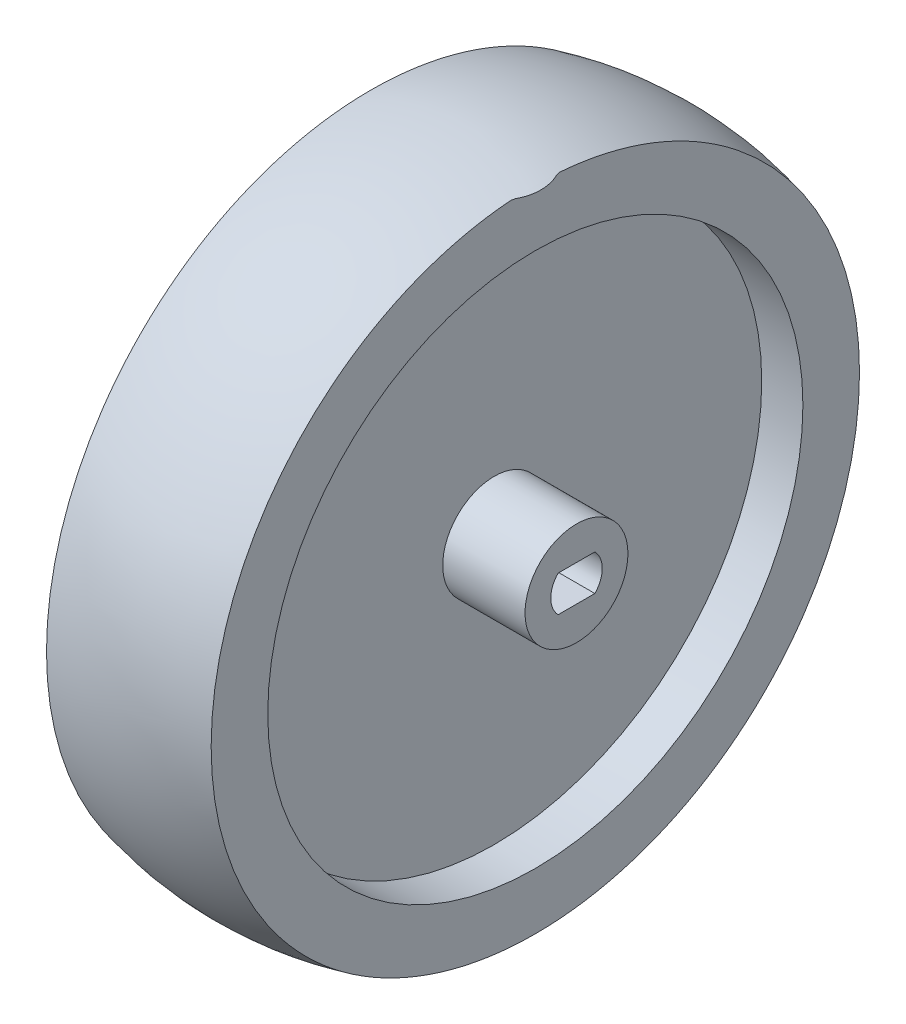
SolidWorks part; units mm, degrees
ref_plane "前视基准面" through (0, 0, 0) normal (0, 0, 1) x (1, 0, 0)
ref_plane "上视基准面" through (0, 0, 0) normal (0, 1, 0) x (1, 0, 0)
ref_plane "右视基准面" through (0, 0, 0) normal (1, 0, 0) x (0, 0, -1)
other "Configuration Table"
sketch "草图1" plane through (0, 0, 0) normal (0, 0, 1) x (1, 0, 0)
  line L0 (3.8691, 32.2689) -> (-3.8691, -32.2689)
  arc A0 (3.8691, 32.2689) -> (-3.8691, -32.2689) centre (0, 0) ccw
  point P4 (0, 0)
  dimension "D1" = 65
revolve "旋转3" add sketch "草图1" angle 360 about L0
sketch "草图2" plane through (0, 0, 0) normal (0, 1, 0) x (1, 0, 0)
  line L1 (-8, 32.5) -> (8, 32.5)
  line L2 (-8, 32.5) -> (-8, -32.5)
  line L3 (-8, -32.5) -> (8, -32.5)
  line L4 (8, 32.5) -> (8, -32.5)
  line L5 (-8, 32.5) -> (8, -32.5) construction
  line L6 (-8, -32.5) -> (8, 32.5) construction
  circle A0 centre (0, 0) radius 32.5 construction
  point P4 (0, 0)
  point P7 (0, 0)
  dimension "D1" = 16
extrude "切除-拉伸1" cut sketch "草图2" against normal through all and the other way through all flip side to cut
sketch "草图3" plane through (8, 0, 0) normal (1, 0, 0) x (0, 0, -1)
  circle A0 centre (0, 0) radius 26
  dimension "D1" = 52
extrude "切除-拉伸2" cut sketch "草图3" against normal blind 4
sketch "草图4" plane through (-8, 0, 0) normal (-1, 0, 0) x (0, 0, 1)
  circle A0 centre (0, 0) radius 26 construction
  circle A3 centre (0, 0) radius 26
extrude "切除-拉伸3" cut sketch "草图4" against normal blind 4
sketch "草图5" plane through (4, 0, 0) normal (1, 0, 0) x (0, 0, -1)
  line L0 (-1.7854, 1.75) -> (1.7854, 1.75)
  line L2 (1.7854, -1.75) -> (-1.7854, -1.75)
  circle A0 centre (0, 0) radius 5
  arc A1 (-1.7854, 1.75) -> (-1.7854, -1.75) centre (0, 0) ccw
  arc A2 (1.7854, -1.75) -> (1.7854, 1.75) centre (0, 0) ccw
  point P8 (0, 0)
  dimension "D1" = 10
  dimension "D2" = 5
  dimension "D3" = 3.5
  dimension "D4" = 1.75
extrude "凸台-拉伸2" add sketch "草图5" along normal blind 8
sketch "草图6" plane through (-8, 0, 0) normal (-1, 0, 0) x (0, 0, 1)
  circle A0 centre (0, 0) radius 4.25
  dimension "D1" = 8.5
extrude "切除-拉伸6" cut sketch "草图6" against normal blind 4 from surface at -4 starting at face at (-4, 0, 26)
sketch "草图7" plane through (0, 0, 0) normal (-1, 0, 0) x (0, 0, 1)
  line L0 (-1.7854, 1.75) -> (1.7854, 1.75) construction
  circle A0 centre (0, 0) radius 1.75
extrude "切除-拉伸7" cut sketch "草图7" against normal through all
